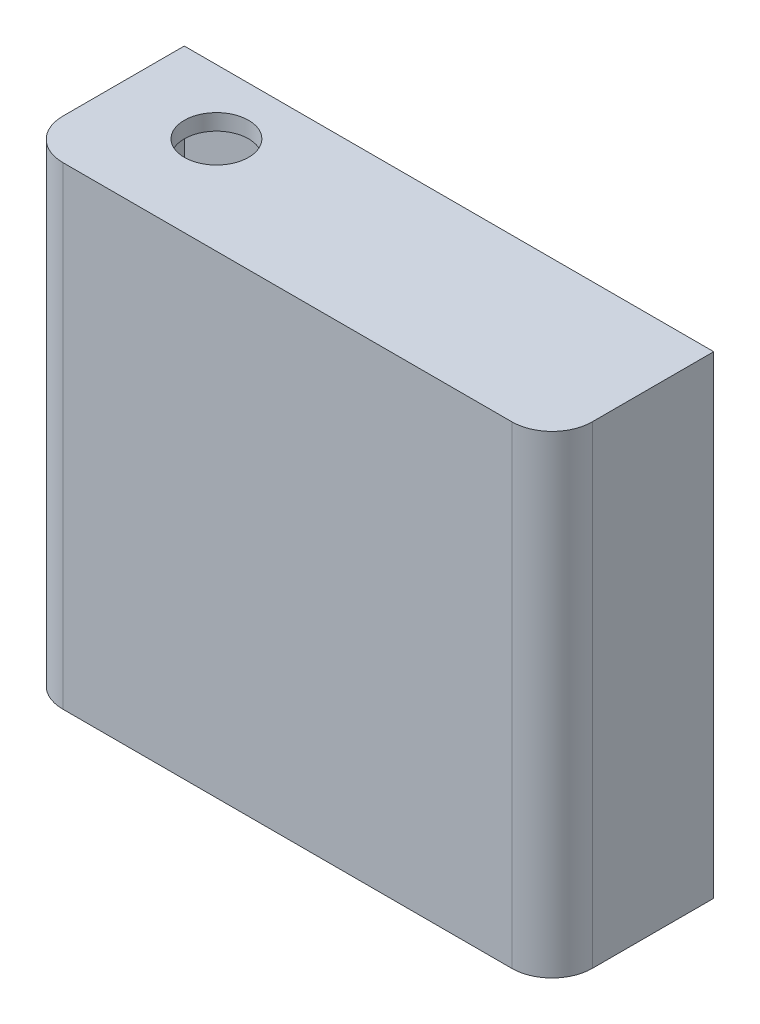
SolidWorks part; units mm, degrees
ref_plane "Спереди" through (0, 0, 0) normal (0, 0, 1) x (1, 0, 0)
ref_plane "Сверху" through (0, 0, 0) normal (0, 1, 0) x (1, 0, 0)
ref_plane "Справа" through (0, 0, 0) normal (1, 0, 0) x (0, 0, -1)
sketch "Эскиз1" plane through (0, 0, -15.113) normal (0, 0, -1) x (-1, 0, 0)
  line L0 (-40.734, 56.896) -> (-20.734, 56.896) construction
  line L1 (-63.668, 56.896) -> (2.2, 56.896)
  line L2 (-63.668, 56.896) -> (-63.668, 0)
  line L3 (2.2, 56.896) -> (2.2, 0)
  line L12 (-63.668, 0) -> (2.2, 0)
  line L13 (-61.468, 56.896) -> (0, 56.896) construction
  line L14 (-61.468, 0) -> (-61.468, 56.896) construction
  line L16 (0, 0) -> (-61.468, 0) construction
  point P0 (-30.734, 56.896)
  dimension "D1" = 2.2
extrude "Бобышка-Вытянуть1" add sketch "Эскиз1" along normal blind 2
sketch "Эскиз2" plane through (0, 0, -17.113) normal (0, 0, -1) x (-1, 0, 0)
  line L0 (-21.314, 34.396) -> (-22.854, 34.396) construction
  line L1 (-20.084, 40.396) -> (-1.8, 40.396)
  line L2 (-20.084, 40.396) -> (-24.084, 40.396)
  line L3 (-20.084, 40.396) -> (-20.084, 28.396) construction
  line L4 (-20.084, 28.396) -> (-24.084, 28.396)
  line L5 (-24.084, 40.396) -> (-24.084, 28.396)
  line L6 (-20.084, 40.396) -> (-24.084, 28.396) construction
  line L7 (-20.084, 28.396) -> (-24.084, 40.396) construction
  line L8 (-1.8, 40.396) -> (-1.8, 28.396)
  line L9 (-1.8, 28.396) -> (-20.084, 28.396)
  line L10 (2.2, 0) -> (2.2, 56.896) construction
  point P0 (-22.084, 34.396)
  point P1 (-22.084, 34.396)
  dimension "D1" = 12
  dimension "D2" = 4
  dimension "D3" = 4
extrude "Вырез-Вытянуть1" cut sketch "Эскиз2" against normal through all both and the other way through all
sketch "Эскиз3" plane through (0, 0, -15.113) normal (0, 0, 1) x (1, 0, 0)
  line L0 (-2.2, 56.896) -> (-2.2, 0)
  line L1 (-2.2, 56.896) -> (-0.2, 56.896)
  line L2 (-2.2, 0) -> (-0.2, 0)
  line L3 (-0.2, 56.896) -> (-0.2, 0)
  line L4 (63.668, 56.896) -> (63.668, 0)
  line L5 (63.668, 56.896) -> (61.668, 56.896)
  line L6 (63.668, 0) -> (61.668, 0)
  line L7 (61.668, 56.896) -> (61.668, 0)
  point P0 (58.4043, 56.896)
  dimension "D1" = 2
extrude "Бобышка-Вытянуть2" add sketch "Эскиз3" along normal offset from surface (18.113 mm away) 3
sketch "Эскиз4" plane through (0, 0, 3) normal (0, 0, 1) x (1, 0, 0)
  line L0 (-2.2, 0) -> (63.668, 0)
  line L1 (-2.2, 0) -> (-2.2, 56.896)
  line L2 (63.668, 0) -> (63.668, 56.896)
  line L3 (-2.2, 56.896) -> (63.668, 56.896)
  point P0 (63.668, 56.896)
extrude "Бобышка-Вытянуть3" add sketch "Эскиз4" against normal blind 2
sketch "Эскиз5" plane through (0, 56.896, 0) normal (0, 1, 0) x (1, 0, 0)
  line L4 (-2.2, 17.113) -> (-2.2, -3)
  line L5 (-2.2, -3) -> (63.668, -3)
  line L6 (63.668, -3) -> (63.668, 17.113)
  line L7 (63.668, 17.113) -> (-2.2, 17.113)
  line L8 (-2.2, 17.113) -> (-2.2, -3)
  line L9 (-2.2, -3) -> (63.668, -3)
  line L10 (63.668, -3) -> (63.668, 17.113)
  line L11 (63.668, 17.113) -> (-2.2, 17.113)
  dimension "D1" = 0
extrude "Бобышка-Вытянуть4" add sketch "Эскиз5" along normal blind 2
fillet "Скругление1" radius 5 4 edges at (-2.2, 29.448, 3) (63.668, 29.448, 3) (-0.2, 28.448, 1) (61.668, 28.448, 1)
sketch "Эскиз6" plane through (0, 58.896, 0) normal (0, 1, 0) x (1, 0, 0)
  line L0 (63.668, 17.113) -> (-2.2, 17.113) construction
  line L2 (-2.2, 17.113) -> (-2.2, 2) construction
  circle A0 centre (9.8, 9.113) radius 4
  dimension "D1" = 8
  dimension "D2" = 8
  dimension "D3" = 12
extrude "Вырез-Вытянуть2" cut sketch "Эскиз6" against normal through all both and the other way through all
